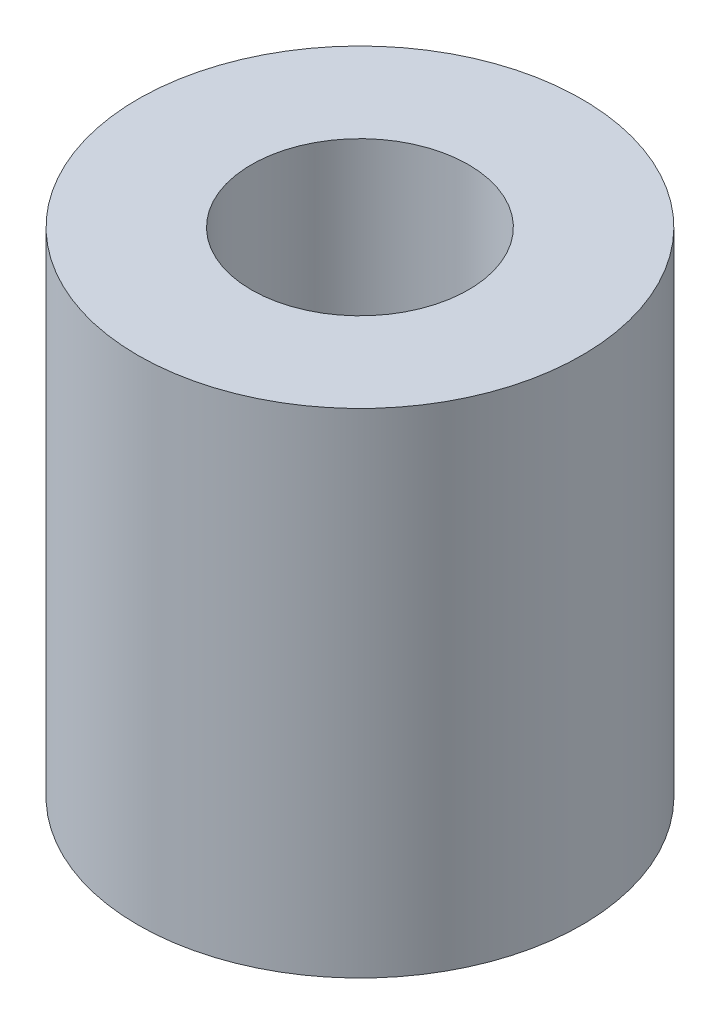
SolidWorks part; units mm, degrees
ref_plane "Front Plane" through (0, 0, 0) normal (0, 0, 1) x (1, 0, 0)
ref_plane "Top Plane" through (0, 0, 0) normal (0, 1, 0) x (1, 0, 0)
ref_plane "Right Plane" through (0, 0, 0) normal (1, 0, 0) x (0, 0, -1)
sketch "Sketch1" plane through (0, 0, 0) normal (0, 1, 0) x (1, 0, 0)
  circle A0 centre (0, 0) radius 2.25
  circle A2 centre (0, 0) radius 1.1
extrude "Boss-Extrude1" add sketch "Sketch1" along normal blind 5
